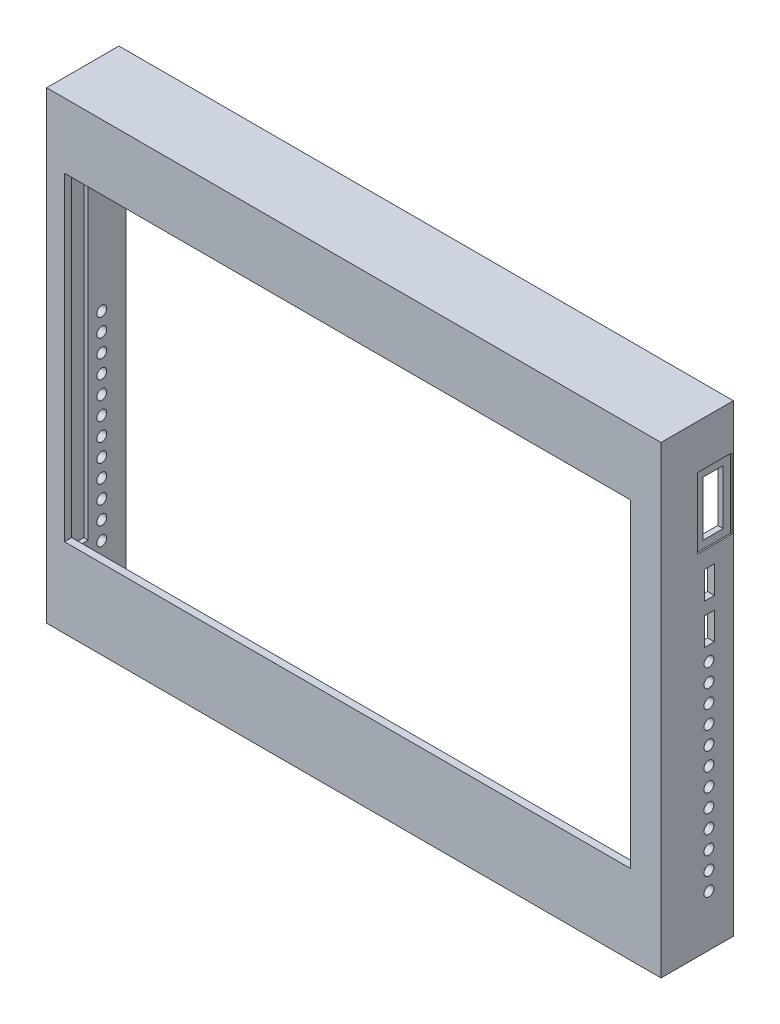
SolidWorks part; units mm, degrees
ref_plane "前视基准面" through (0, 0, 0) normal (0, 0, 1) x (1, 0, 0)
ref_plane "上视基准面" through (0, 0, 0) normal (0, 1, 0) x (1, 0, 0)
ref_plane "右视基准面" through (0, 0, 0) normal (1, 0, 0) x (0, 0, -1)
sketch "草图1" plane through (0, 0, 0) normal (0, 0, 1) x (1, 0, 0)
  line L1 (-85.3651, 45.1933) -> (89.2949, 45.1933)
  line L2 (-85.3651, 45.1933) -> (-85.3651, -83.1367)
  line L3 (-85.3651, -83.1367) -> (89.2949, -83.1367)
  line L4 (89.2949, 45.1933) -> (89.2949, -83.1367)
  dimension "D1" = 174.66
  dimension "D2" = 128.33
extrude "凸台-拉伸1" add sketch "草图1" along normal blind 20
sketch "草图2" plane through (0, 0, 20) normal (0, 0, 1) x (1, 0, 0)
  line L0 (89.2949, 45.1933) -> (-85.3651, 45.1933) construction
  line L1 (-77.3651, 27.1933) -> (79.2949, 27.1933)
  line L2 (-77.3651, 27.1933) -> (-77.3651, -61.1367)
  line L3 (-77.3651, -61.1367) -> (79.2949, -61.1367)
  line L4 (79.2949, 27.1933) -> (79.2949, -61.1367)
  line L6 (-85.3651, -83.1367) -> (89.2949, -83.1367) construction
  line L7 (-85.3651, 45.1933) -> (-85.3651, -83.1367) construction
  line L8 (89.2949, -83.1367) -> (89.2949, 45.1933) construction
  dimension "D1" = 18
  dimension "D2" = 22
  dimension "D3" = 8
  dimension "D4" = 10
sketch "草图4" plane through (0, 0, 0) normal (0, 0, -1) x (-1, 0, 0)
  line L0 (-89.2949, 45.1933) -> (85.3651, 45.1933) construction
  line L1 (-85.7949, 29.1933) -> (78.7151, 29.1933)
  line L2 (-85.7949, 29.1933) -> (-85.7949, -71.1367)
  line L3 (-85.7949, -71.1367) -> (-61.7949, -71.1367)
  line L4 (78.7151, 29.1933) -> (78.7151, -71.1367)
  line L5 (85.3651, -83.1367) -> (-89.2949, -83.1367) construction
  line L6 (-89.2949, -83.1367) -> (-89.2949, 45.1933) construction
  line L7 (85.3651, 45.1933) -> (85.3651, -83.1367) construction
  line L8 (-16.7949, -71.1367) -> (78.7151, -71.1367)
  line L13 (-61.7949, -74.1367) -> (-16.7949, -74.1367)
  line L14 (-61.7949, -74.1367) -> (-61.7949, -71.1367)
  line L16 (-16.7949, -74.1367) -> (-16.7949, -71.1367)
  dimension "D1" = 16
  dimension "D2" = 12
  dimension "D3" = 3.5
  dimension "D4" = 6.65
  dimension "D6" = 3
  dimension "D7" = 45
extrude "切除-拉伸2" cut sketch "草图4" against normal blind 8
sketch "草图5" plane through (0, 0, 0) normal (0, 0, -1) x (-1, 0, 0)
  line L0 (-89.2949, -83.1367) -> (-89.2949, 45.1933) construction
  line L1 (-76.8949, 34.8542) -> (71.5051, 34.8542)
  line L2 (-85.6949, 34.8542) -> (-85.6949, -72.1458)
  line L3 (-77.7949, -72.1458) -> (69.5051, -72.1458)
  line L4 (80.3051, 34.8542) -> (80.3051, -72.1458)
  line L6 (-85.6949, 34.8542) -> (-85.6949, 43.6542)
  line L7 (-85.6949, 43.6542) -> (-76.8949, 43.6542)
  line L8 (-76.8949, 34.8542) -> (-76.8949, 43.6542)
  line L10 (80.3051, 34.8542) -> (80.3051, 43.6542)
  line L11 (80.3051, 43.6542) -> (71.5051, 43.6542)
  line L12 (71.5051, 34.8542) -> (71.5051, 43.6542)
  line L14 (-85.6949, -72.1458) -> (-85.6949, -80.9458)
  line L15 (-85.6949, -80.9458) -> (-77.7949, -80.9458)
  line L16 (-77.7949, -72.1458) -> (-77.7949, -80.9458)
  line L18 (80.3051, -72.1458) -> (80.3051, -80.9458)
  line L19 (80.3051, -80.9458) -> (69.5051, -80.9458)
  line L20 (69.5051, -72.1458) -> (69.5051, -80.9458)
  dimension "D1" = 107
  dimension "D2" = 166
  dimension "D3" = 197.4968
  dimension "D4" = 8.8
  dimension "D5" = 8.8
  dimension "D6" = 8.8
  dimension "D7" = 8.8
  dimension "D8" = 3.6
extrude "切除-拉伸3" cut sketch "草图5" against normal blind 10.5
sketch "草图6" plane through (89.2949, 0, 0) normal (1, 0, 0) x (0, 0, -1)
  line L1 (-2.4, 30.6542) -> (-8, 30.6542)
  line L2 (-2.4, 30.6542) -> (-2.4, 15.5542)
  line L3 (-2.4, 15.5542) -> (-8, 15.5542)
  line L4 (-8, 30.6542) -> (-8, 15.5542)
  line L5 (-10.5, 43.6542) -> (0, 43.6542) construction
  line L6 (-20, -83.1367) -> (-20, 45.1933) construction
  line L8 (-8, 8.7542) -> (-5.25, 8.7542)
  line L9 (-8, 8.7542) -> (-8, 1.1542)
  line L10 (-8, 1.1542) -> (-5.25, 1.1542)
  line L11 (-5.25, 8.7542) -> (-5.25, 1.1542)
  line L12 (-8, -2.3458) -> (-5.25, -2.3458)
  line L13 (-8, -2.3458) -> (-8, -9.9458)
  line L14 (-8, -9.9458) -> (-5.25, -9.9458)
  line L15 (-5.25, -2.3458) -> (-5.25, -9.9458)
  point P16 (-6.625, -2.3458)
  dimension "D1" = 13
  dimension "D2" = 12
  dimension "D3" = 15.1
  dimension "D4" = 5.6
  dimension "D5" = 7.6
  dimension "D6" = 7.6
  dimension "D7" = 2.75
  dimension "D8" = 2.75
  dimension "D9" = 12
  dimension "D10" = 12
  dimension "D11" = 6.8
  dimension "D12" = 3.5
extrude "切除-拉伸4" cut sketch "草图6" against normal blind 8
sketch "草图7" plane through (89.2949, 0, 0) normal (1, 0, 0) x (0, 0, -1)
  line L0 (-2.4, 30.6542) -> (-8, 15.5542) construction
  line L1 (-0.4396, 32.9287) -> (-9.9396, 32.9287)
  line L2 (-0.4396, 32.9287) -> (-0.4396, 13.4287)
  line L3 (-0.4396, 13.4287) -> (-9.9396, 13.4287)
  line L4 (-9.9396, 32.9287) -> (-9.9396, 13.4287)
  line L5 (-8, 30.6542) -> (-8, 15.5542) construction
  line L6 (-8, 15.5542) -> (-2.4, 15.5542) construction
  line L7 (-2.4, 15.5542) -> (-8, 30.6542) construction
  line L8 (-0.4396, 32.9287) -> (-9.9396, 13.4287) construction
  line L9 (-0.4396, 13.4287) -> (-9.9396, 32.9287) construction
  dimension "D1" = 19.5
  dimension "D2" = 9.5
extrude "切除-拉伸5" cut sketch "草图7" against normal blind 2
sketch "草图8" plane through (89.2949, 0, 0) normal (1, 0, 0) x (0, 0, -1)
  line L1 (-8, -9.9458) -> (-5.25, -9.9458) construction
  circle A0 centre (-6.7555, -13.9458) radius 1.375
  circle A1 centre (-6.7555, -18.9458) radius 1.375
  circle A2 centre (-6.7555, -23.9458) radius 1.375
  circle A3 centre (-6.7555, -28.9458) radius 1.375
  circle A4 centre (-6.7555, -33.9458) radius 1.375
  circle A5 centre (-6.7555, -38.9458) radius 1.375
  circle A6 centre (-6.7555, -43.9458) radius 1.375
  circle A7 centre (-6.7555, -48.9458) radius 1.375
  circle A8 centre (-6.7555, -53.9458) radius 1.375
  circle A9 centre (-6.7555, -58.9458) radius 1.375
  circle A10 centre (-6.7555, -63.9458) radius 1.375
  circle A11 centre (-6.7555, -68.9458) radius 1.375
  dimension "D1" = 2.75
  dimension "D3" = 12
  dimension "D2" = 4
extrude "切除-拉伸6" cut sketch "草图8" against normal through all
sketch "草图9" plane through (0, 0, 0) normal (0, 0, -1) x (-1, 0, 0)
  line L0 (85.3651, -83.1367) -> (-89.2949, -83.1367) construction
  line L1 (-75.7949, -75.6367) -> (67.5051, -75.6367)
  line L2 (-75.7949, -75.6367) -> (-75.7949, -81.1367)
  line L3 (-75.7949, -81.1367) -> (67.5051, -81.1367)
  line L4 (67.5051, -75.6367) -> (67.5051, -81.1367)
  line L5 (-74.8949, 36.8542) -> (69.5051, 36.8542)
  line L6 (-74.8949, 36.8542) -> (-74.8949, 43.1933)
  line L7 (-74.8949, 43.1933) -> (69.5051, 43.1933)
  line L8 (69.5051, 36.8542) -> (69.5051, 43.1933)
  line L9 (-61.7949, -74.1367) -> (-16.7949, -74.1367) construction
  line L10 (-77.7949, -80.9458) -> (-77.7949, -72.1458) construction
  line L11 (69.5051, -72.1458) -> (69.5051, -80.9458) construction
  line L12 (-89.2949, 45.1933) -> (85.3651, 45.1933) construction
  line L13 (71.5051, 34.8542) -> (-76.8949, 34.8542) construction
  line L14 (-76.8949, 34.8542) -> (-76.8949, 43.6542) construction
  line L15 (71.5051, 43.6542) -> (71.5051, 34.8542) construction
  dimension "D1" = 2
  dimension "D2" = 1.5
  dimension "D3" = 2
  dimension "D4" = 2
  dimension "D5" = 2
  dimension "D6" = 2
  dimension "D7" = 2
  dimension "D8" = 2
extrude "切除-拉伸7" cut sketch "草图9" against normal blind 18
extrude "切除-拉伸8" cut sketch "草图2" against normal through all
sketch "草图10" plane through (0, 0, 10.5) normal (0, 0, -1) x (-1, 0, 0)
  line L0 (77.3651, -61.1367) -> (-79.2949, 27.1933) construction
  line L1 (-79.2949, 27.1933) -> (-79.2949, -61.1367) construction
  line L2 (-79.2949, -61.1367) -> (77.3651, 27.1933) construction
  line L4 (81.5351, -66.9717) -> (-83.4649, -66.9717)
  line L5 (81.5351, -66.9717) -> (81.5351, 33.0283)
  line L6 (81.5351, 33.0283) -> (-83.4649, 33.0283)
  line L7 (-83.4649, -66.9717) -> (-83.4649, 33.0283)
  line L8 (81.5351, -66.9717) -> (-83.4649, 33.0283) construction
  line L9 (81.5351, 33.0283) -> (-83.4649, -66.9717) construction
  point P8 (-0.9649, -16.9717)
  dimension "D1" = 165
  dimension "D2" = 100
extrude "切除-拉伸10" cut sketch "草图10" against normal blind 7.5
sketch "草图11" plane through (0, 0, 0) normal (0, 0, -1) x (-1, 0, 0)
  line L0 (-83.4649, -66.9717) -> (81.5351, -66.9717) construction
  line L1 (-16.7949, -74.1367) -> (-61.7865, -74.1367)
  line L2 (-16.7949, -74.1367) -> (-16.7949, -66.9717)
  line L3 (-16.7949, -66.9717) -> (-61.7865, -66.9717)
  line L4 (-61.7865, -74.1367) -> (-61.7865, -66.9717)
extrude "切除-拉伸11" cut sketch "草图11" against normal blind 18
sketch "草图12" plane through (0, 0, 0) normal (0, 0, -1) x (-1, 0, 0)
  line L1 (80.3051, -80.9458) -> (-85.6949, -80.9458)
  line L2 (80.3051, -80.9458) -> (80.3051, 43.6542)
  line L3 (80.3051, 43.6542) -> (-85.6949, 43.6542)
  line L4 (-85.6949, -80.9458) -> (-85.6949, 43.6542)
extrude "切除-拉伸12" cut sketch "草图12" against normal blind 13
sketch "草图13" plane through (0, 0, 13) normal (0, 0, -1) x (-1, 0, 0)
  line L14 (-85.6949, 43.6542) -> (-85.6949, -80.9458) construction
  line L15 (72.3051, -80.9458) -> (-77.6949, -80.9458)
  line L16 (72.3051, -80.9458) -> (72.3051, 43.6542)
  line L17 (72.3051, 43.6542) -> (-77.6949, 43.6542)
  line L18 (-77.6949, -80.9458) -> (-77.6949, 43.6542)
  line L19 (80.3051, -80.9458) -> (80.3051, 43.6542) construction
  line L20 (-85.6949, -80.9458) -> (-75.7949, -80.9458) construction
  line L21 (80.3051, 43.6542) -> (-85.6949, 43.6542) construction
  dimension "D1" = 8
  dimension "D2" = 8
  dimension "D3" = 0
  dimension "D4" = 0
extrude "切除-拉伸15" cut sketch "草图13" against normal blind 5
sketch "草图14" plane through (0, 0, 13) normal (0, 0, -1) x (-1, 0, 0)
  line L8 (72.3051, 33.0283) -> (72.3051, 43.6542) construction
  line L9 (72.3051, 31.6542) -> (80.3051, 31.6542)
  line L10 (72.3051, 31.6542) -> (72.3051, -69.3458)
  line L11 (72.3051, -69.3458) -> (80.3051, -69.3458)
  line L12 (80.3051, 31.6542) -> (80.3051, -69.3458)
  line L13 (80.3051, -80.9458) -> (80.3051, -66.9717) construction
  line L14 (80.3051, 43.6542) -> (72.3051, 43.6542) construction
  line L15 (72.3051, -80.9458) -> (80.3051, -80.9458) construction
  line L16 (-77.6949, -66.9717) -> (-77.6949, -80.9458) construction
  line L17 (-77.6949, -69.3458) -> (-85.6949, -69.3458)
  line L18 (-77.6949, -69.3458) -> (-77.6949, 31.6542)
  line L19 (-77.6949, 31.6542) -> (-85.6949, 31.6542)
  line L20 (-85.6949, -69.3458) -> (-85.6949, 31.6542)
  line L21 (-85.6949, 43.6542) -> (-85.6949, -80.9458) construction
  line L22 (-85.6949, -80.9458) -> (-77.6949, -80.9458) construction
  line L23 (-77.6949, 43.6542) -> (-85.6949, 43.6542) construction
  dimension "D1" = 11.6
  dimension "D2" = 12
  dimension "D3" = 11.6
  dimension "D4" = 12
extrude "切除-拉伸16" cut sketch "草图14" against normal blind 5
sketch "草图15" plane through (0, 0, 0) normal (0, 0, -1) x (-1, 0, 0)
  line L0 (-89.2949, 45.1933) -> (85.3651, 45.1933) construction
  line L1 (85.3651, -83.1367) -> (82.3051, -83.1367)
  line L2 (85.3651, -83.1367) -> (85.3651, 45.1933)
  line L3 (85.3651, 45.1933) -> (82.3051, 45.1933)
  line L4 (82.3051, -83.1367) -> (82.3051, 45.1933)
  line L5 (80.3051, -80.9458) -> (80.3051, 43.6542) construction
  line L6 (-85.6949, 31.6542) -> (-85.6949, -69.3458) construction
  line L7 (-89.2949, -83.1367) -> (-87.6949, -83.1367)
  line L8 (-89.2949, -83.1367) -> (-89.2949, 45.1933)
  line L9 (-89.2949, 45.1933) -> (-87.6949, 45.1933)
  line L10 (-87.6949, -83.1367) -> (-87.6949, 45.1933)
  dimension "D1" = 2
  dimension "D2" = 2
extrude "切除-拉伸17" cut sketch "草图15" against normal through all
sketch "草图16" plane through (0, 0, 13) normal (0, 0, -1) x (-1, 0, 0)
  line L0 (-85.6949, -69.3458) -> (-85.6949, -80.9458) construction
  line L1 (72.3051, -69.3458) -> (80.3051, -69.3458)
  line L2 (72.3051, -69.3458) -> (72.3051, -80.9458)
  line L3 (72.3051, -80.9458) -> (80.3051, -80.9458)
  line L4 (80.3051, -69.3458) -> (80.3051, -80.9458)
  line L5 (-77.6949, -69.3458) -> (-85.6949, -69.3458)
  line L6 (-77.6949, -69.3458) -> (-77.6949, -80.9458)
  line L7 (-77.6949, -80.9458) -> (-85.6949, -80.9458)
  line L8 (-85.6949, -69.3458) -> (-85.6949, -80.9458)
  line L9 (-85.6949, -71.1367) -> (-85.6949, -80.9458) construction
  line L10 (80.3051, 43.6542) -> (-85.6949, 43.6542) construction
  line L11 (72.3051, 33.0283) -> (80.3051, 33.0283)
  line L12 (72.3051, 33.0283) -> (72.3051, 43.6542)
  line L13 (72.3051, 43.6542) -> (80.3051, 43.6542)
  line L14 (80.3051, 33.0283) -> (80.3051, 43.6542)
  line L15 (80.3051, 43.6542) -> (72.3051, 43.6542) construction
  line L17 (-77.6949, 43.6542) -> (-85.6949, 43.6542)
  line L18 (-77.6949, 43.6542) -> (-77.6949, 33.0283)
  line L19 (-77.6949, 33.0283) -> (-85.6949, 33.0283)
  line L20 (-85.6949, 43.6542) -> (-85.6949, 33.0283)
extrude "凸台-拉伸2" add sketch "草图16" along normal blind 3.2
